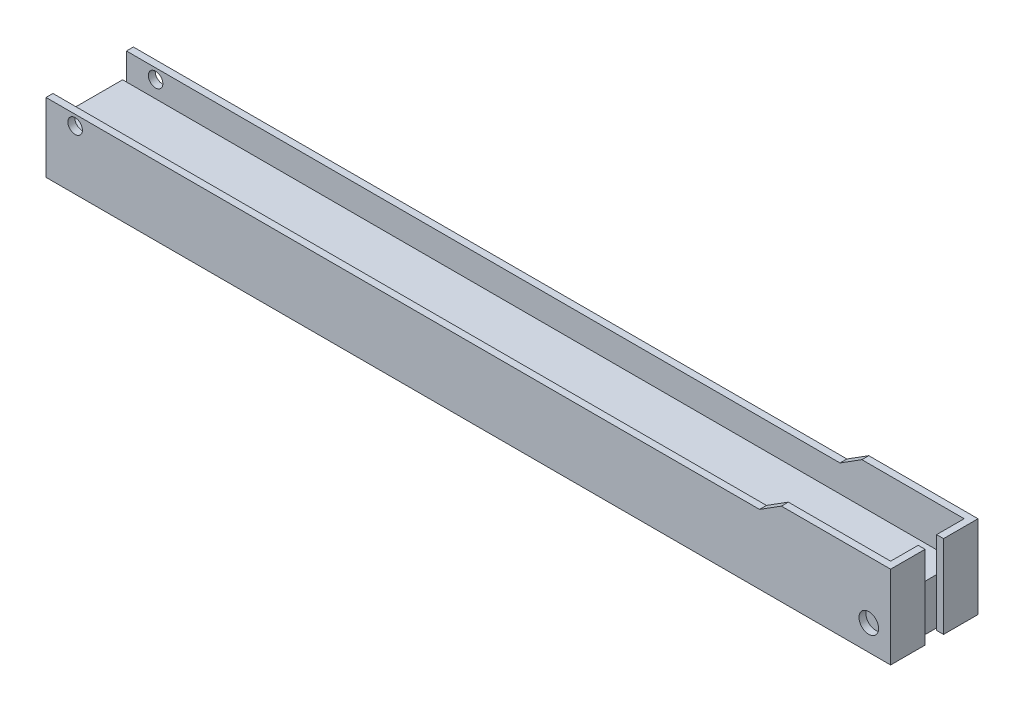
SolidWorks part; units mm, degrees
ref_plane "Front Plane" through (0, 0, 0) normal (0, 0, 1) x (1, 0, 0)
ref_plane "Top Plane" through (0, 0, 0) normal (0, 1, 0) x (1, 0, 0)
ref_plane "Right Plane" through (0, 0, 0) normal (1, 0, 0) x (0, 0, -1)
sketch "Sketch1" plane through (0, 0, 0) normal (0, 1, 0) x (1, 0, 0)
  line L1 (-73.66, 7.62) -> (73.66, 7.62)
  line L2 (-73.66, 7.62) -> (-73.66, -7.62)
  line L3 (-73.66, -7.62) -> (73.66, -7.62)
  line L4 (73.66, 7.62) -> (73.66, -7.62)
  line L5 (-73.66, 7.62) -> (73.66, -7.62) construction
  line L6 (-73.66, -7.62) -> (73.66, 7.62) construction
  point P0 (0, 0)
  dimension "D1" = 15.24
  dimension "D2" = 147.32
extrude "Boss-Extrude1" add sketch "Sketch1" along normal blind 14.478
sketch "Sketch3" plane through (-73.66, 0, 0) normal (-1, 0, 0) x (0, 0, 1)
  line L0 (-6.4135, 13.2715) -> (-6.4135, 1.2065)
  line L1 (-7.62, 14.478) -> (7.62, 14.478)
  line L2 (-7.62, 14.478) -> (-7.62, 0)
  line L3 (-7.62, 0) -> (7.62, 0)
  line L4 (7.62, 14.478) -> (7.62, 0)
  line L6 (6.4135, 13.2715) -> (6.4135, 1.2065)
  line L8 (-6.4135, 13.2715) -> (-6.4135, 14.478)
  line L9 (-6.4135, 14.478) -> (6.4135, 14.478)
  line L10 (6.4135, 14.478) -> (6.4135, 13.2715)
  line L12 (-6.4135, 13.2715) -> (6.4135, 13.2715) construction
  line L15 (6.4135, 1.2065) -> (4.6771, 1.2065) construction
  line L16 (4.6771, 1.2065) -> (4.6771, 1.7145) construction
  line L21 (-6.4135, 1.2065) -> (6.4135, 1.2065) construction
  line L23 (-6.4135, 1.2065) -> (6.4135, 1.2065)
  line L24 (4.6771, 1.7145) -> (5.9471, 1.7145) construction
  line L25 (5.9471, 1.7145) -> (5.9471, 8.0645) construction
  line L26 (5.9471, 8.0645) -> (-5.7369, 8.0645) construction
  line L27 (4.6771, 1.2065) -> (4.6771, 1.7145)
  line L28 (4.6771, 1.7145) -> (5.9471, 1.7145)
  line L29 (5.9471, 1.7145) -> (5.9471, 8.0645)
  line L30 (5.9471, 8.0645) -> (-5.7369, 8.0645)
  line L31 (-5.7369, 8.0645) -> (-5.7369, 1.7145)
  line L32 (-5.7369, 1.7145) -> (-4.4669, 1.7145)
  line L33 (-4.4669, 1.7145) -> (-4.4669, 1.2065)
  line L34 (4.1691, 1.2065) -> (4.1691, 2.2225)
  line L35 (4.1691, 2.2225) -> (5.4391, 2.2225)
  line L36 (5.4391, 2.2225) -> (5.4391, 7.5565)
  line L37 (5.4391, 7.5565) -> (-5.2289, 7.5565)
  line L38 (-5.2289, 7.5565) -> (-5.2289, 2.2225)
  line L39 (-5.2289, 2.2225) -> (-3.9589, 2.2225)
  line L40 (-3.9589, 2.2225) -> (-3.9589, 1.2065)
  dimension "D2" = 6.35
  dimension "D3" = 0.508
  dimension "D5" = 11.684
  dimension "D6" = 0.508
  dimension "D4" = 1.27
  dimension "D1" = 1.2065
extrude "Cut-Extrude2" cut sketch "Sketch3" against normal blind 146.1135
sketch "Sketch5" plane through (73.66, 0, 0) normal (1, 0, 0) x (0, 0, -1)
  line L0 (0, 0) -> (0, 14.478) construction
  line L1 (-7.62, 14.478) -> (7.62, 14.478) construction
  line L2 (0.508, 0) -> (0.508, 14.478)
  line L3 (-0.508, 0) -> (-0.508, 14.478)
  line L4 (-0.508, 14.478) -> (0.508, 14.478)
  line L5 (-0.508, 0) -> (0.508, 0)
  dimension "D1" = 0.508
  dimension "D2" = 0.508
sketch "Sketch7" plane through (0, 0, 7.62) normal (0, 0, 1) x (1, 0, 0)
  line L0 (73.66, 14.478) -> (54.61, 14.478)
  line L1 (-73.66, 14.478) -> (73.66, 14.478) construction
  line L2 (54.61, 14.478) -> (50.8, 12.0746)
  line L3 (50.8, 12.0746) -> (-73.66, 12.0746)
  line L4 (-73.66, 14.478) -> (-73.66, 0) construction
  line L5 (-73.66, 12.0746) -> (-73.66, 0)
  line L6 (-73.66, 0) -> (73.66, 0)
  line L7 (73.66, 0) -> (73.66, 14.478)
  line L8 (73.66, 0) -> (73.66, 4.445) construction
  line L9 (73.66, 4.445) -> (69.85, 4.445) construction
  line L10 (69.85, 4.445) -> (69.85, 0) construction
  line L11 (-73.66, 12.0746) -> (-73.66, 14.478)
  line L12 (-73.66, 14.478) -> (54.61, 14.478)
  circle A0 centre (69.85, 4.445) radius 1.7145
  line M12 (73.66, 14.478) -> (-73.66, 14.478)
  line M13 (-73.66, 14.478) -> (-73.66, 0)
  dimension "D5" = 3.429
  dimension "D1" = 124.46
  dimension "D2" = 19.05
  dimension "D3" = 4.445
  dimension "D4" = 3.81
extrude "Cut-Extrude5" cut sketch "Sketch7" against normal up to next contours L3 L2 M12 M13 | A0
sketch "Sketch9" plane through (0, 0, 7.62) normal (0, 0, 1) x (1, 0, 0)
  line L0 (-73.66, 12.0746) -> (-68.58, 12.0746) construction
  line L1 (50.8, 12.0746) -> (-73.66, 12.0746) construction
  line L2 (-68.58, 12.0746) -> (-68.58, 10.2966) construction
  circle A0 centre (-68.58, 10.2966) radius 1.27
  dimension "D3" = 2.54
  dimension "D1" = 5.08
  dimension "D2" = 1.778
extrude "Cut-Extrude6" cut sketch "Sketch9" against normal through all
sketch "Sketch10" plane through (0, 8.0645, 0) normal (0, 1, 0) x (1, 0, 0)
  line L0 (168.0223, 0) -> (-168.0223, 0) construction
  point P4 (0, 0)
sketch "Sketch11" plane through (0, 8.0645, 0) normal (0, 1, 0) x (1, 0, 0)
  line L0 (72.4535, 5.7369) -> (-73.66, 5.7369) construction
  line L1 (72.4535, -5.9471) -> (72.0725, -5.9471)
  line L2 (72.4535, -5.9471) -> (72.4535, 5.7369)
  line L3 (72.4535, 5.7369) -> (72.0725, 5.7369)
  line L4 (72.0725, -5.9471) -> (72.0725, 5.7369)
  dimension "D2" = 0.381
extrude "Cut-Extrude7" cut sketch "Sketch11" against normal up to next
sketch "Sketch12" plane through (0, 1.2065, 0) normal (0, 1, 0) x (1, 0, 0)
  line L0 (72.0725, 5.7369) -> (72.0725, 6.4135)
  line L1 (72.4535, 6.4135) -> (-73.66, 6.4135) construction
  line L2 (72.0725, 6.4135) -> (72.4535, 6.4135)
  line L3 (72.4535, 6.4135) -> (-73.66, 6.4135) construction
  line L4 (72.4535, 6.4135) -> (72.4535, 5.7369)
  line L5 (72.4535, 5.7369) -> (72.0725, 5.7369)
extrude "Cut-Extrude8" cut sketch "Sketch12" against normal up to next
sketch "Sketch13" plane through (0, 1.2065, 0) normal (0, 1, 0) x (1, 0, 0)
  line L1 (72.0725, -5.9471) -> (72.4535, -5.9471)
  line L2 (72.0725, -5.9471) -> (72.0725, -6.4135)
  line L3 (72.0725, -6.4135) -> (72.4535, -6.4135)
  line L4 (72.4535, -5.9471) -> (72.4535, -6.4135)
extrude "Cut-Extrude9" cut sketch "Sketch13" against normal up to next
sketch "Sketch14" plane through (73.66, 0, 0) normal (1, 0, 0) x (0, 0, -1)
  line L0 (0, -19.5495) -> (0, 19.5495) construction
  line L1 (1.6129, -19.5495) -> (1.6129, 19.5495)
  line L2 (-1.6129, -19.5495) -> (-1.6129, 19.5495)
  line L3 (-1.6129, 14.478) -> (1.6129, 14.478)
  line L4 (-7.62, 14.478) -> (7.62, 14.478) construction
  line L5 (1.6129, 14.478) -> (1.6129, 0)
  line L6 (1.6129, 0) -> (-1.6129, 0)
  line L7 (-1.6129, 0) -> (-1.6129, 14.478)
  point P4 (0, 0)
  line M2 (-7.62, 0) -> (7.62, 0)
  line M4 (7.62, 14.478) -> (-7.62, 14.478)
  dimension "D1" = 1.6129
  dimension "D2" = 1.6129
extrude "Cut-Extrude10" cut sketch "Sketch14" against normal up to next contours L0 L6 L1 M4 | L0 L3 L2 M2
ref_plane "Plane6" through (0, 0, 0) normal (0, 0, -1) x (-1, 0, 0)
mirror "Mirror1" about plane through (0, 0, 0) normal (0, 0, -1) of "Cut-Extrude5"
